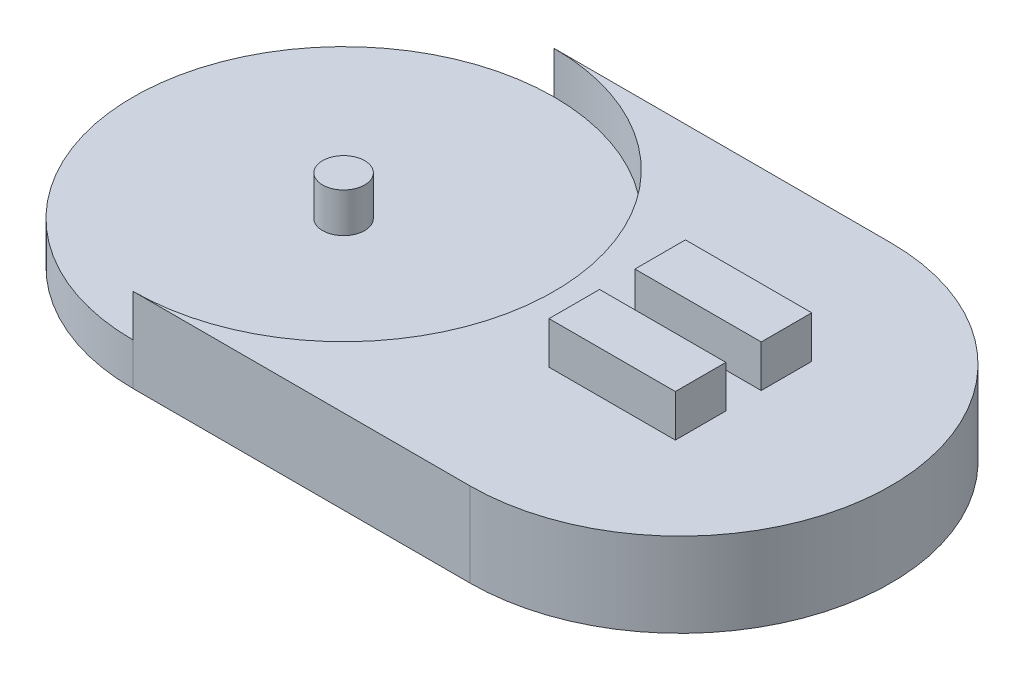
SolidWorks part; units mm, degrees
ref_plane "前基準面" through (0, 0, 0) normal (0, 0, 1) x (1, 0, 0)
ref_plane "上基準面" through (0, 0, 0) normal (0, 1, 0) x (1, 0, 0)
ref_plane "右基準面" through (0, 0, 0) normal (1, 0, 0) x (0, 0, -1)
sketch "草圖1" plane through (0, 0, 0) normal (0, 1, 0) x (1, 0, 0)
  line L0 (0, 25) -> (0, -25) construction
  line L1 (0, 25) -> (40, 25)
  line L2 (0, -25) -> (40, -25)
  arc A0 (0, 25) -> (0, -25) centre (0, 0) ccw
  arc A1 (40, -25) -> (40, 25) centre (40, 0) ccw
  dimension "D1" = 50
  dimension "D3" = 40
  dimension "D2" = 2
extrude "填料-伸長1" add sketch "草圖1" along normal blind 10
sketch "草圖2" plane through (0, 10, 0) normal (0, 1, 0) x (1, 0, 0)
  line L0 (-25, 0) -> (65, 0) construction
  line L1 (65, 0) -> (0, 0) construction
  line L2 (0, 0) -> (0, 25) construction
  arc A0 (0, 25) -> (0, -25) centre (0, 0) ccw construction
  arc A1 (40, -25) -> (40, 25) centre (40, 0) ccw construction
  circle A2 centre (0, 0) radius 25
  dimension "D1" = 50
extrude "除料-伸長1" cut sketch "草圖2" against normal blind 5
sketch "草圖3" plane through (0, 5, 0) normal (0, 1, 0) x (1, 0, 0)
  line L0 (-25, 0) -> (25, 0) construction
  line L1 (25, 0) -> (0, 0) construction
  line L2 (0, 0) -> (0, 25) construction
  arc A0 (0, 25) -> (0, -25) centre (0, 0) ccw construction
  arc A1 (0, -25) -> (0, 25) centre (0, 0) ccw construction
  circle A2 centre (0, 0) radius 2.5
  dimension "D1" = 5
extrude "填料-伸長2" add sketch "草圖3" along normal blind 4.7
sketch "草圖4" plane through (0, 10, 0) normal (0, 1, 0) x (1, 0, 0)
  line L0 (-25, 0) -> (65, 0) construction
  line L1 (40, 8.1) -> (40, 2.1) construction
  line L2 (32.5, 8.1) -> (47.5, 8.1)
  line L3 (32.5, 8.1) -> (32.5, 2.1)
  line L4 (32.5, 2.1) -> (47.5, 2.1)
  line L5 (47.5, 8.1) -> (47.5, 2.1)
  line L6 (32.5, -2.1) -> (47.5, -2.1)
  line L7 (32.5, -2.1) -> (32.5, -8.1)
  line L8 (32.5, -8.1) -> (47.5, -8.1)
  line L9 (47.5, -2.1) -> (47.5, -8.1)
  line L10 (40, -2.1) -> (40, -8.1) construction
  line L11 (32.5, 5.1) -> (47.5, 5.1) construction
  line L12 (32.5, -5.1) -> (47.5, -5.1) construction
  arc A0 (0, 25) -> (0, -25) centre (0, 0) ccw construction
  arc A1 (40, -25) -> (40, 25) centre (40, 0) ccw construction
  point P24 (40, -5.1)
  point P26 (40, 5.1)
  dimension "D1" = 15
  dimension "D2" = 6
  dimension "D3" = 15
  dimension "D4" = 6
  dimension "D5" = 4.2
  dimension "D6" = 40
  dimension "D7" = 40
  dimension "D8" = 2.1
extrude "填料-伸長3" add sketch "草圖4" along normal blind 5
